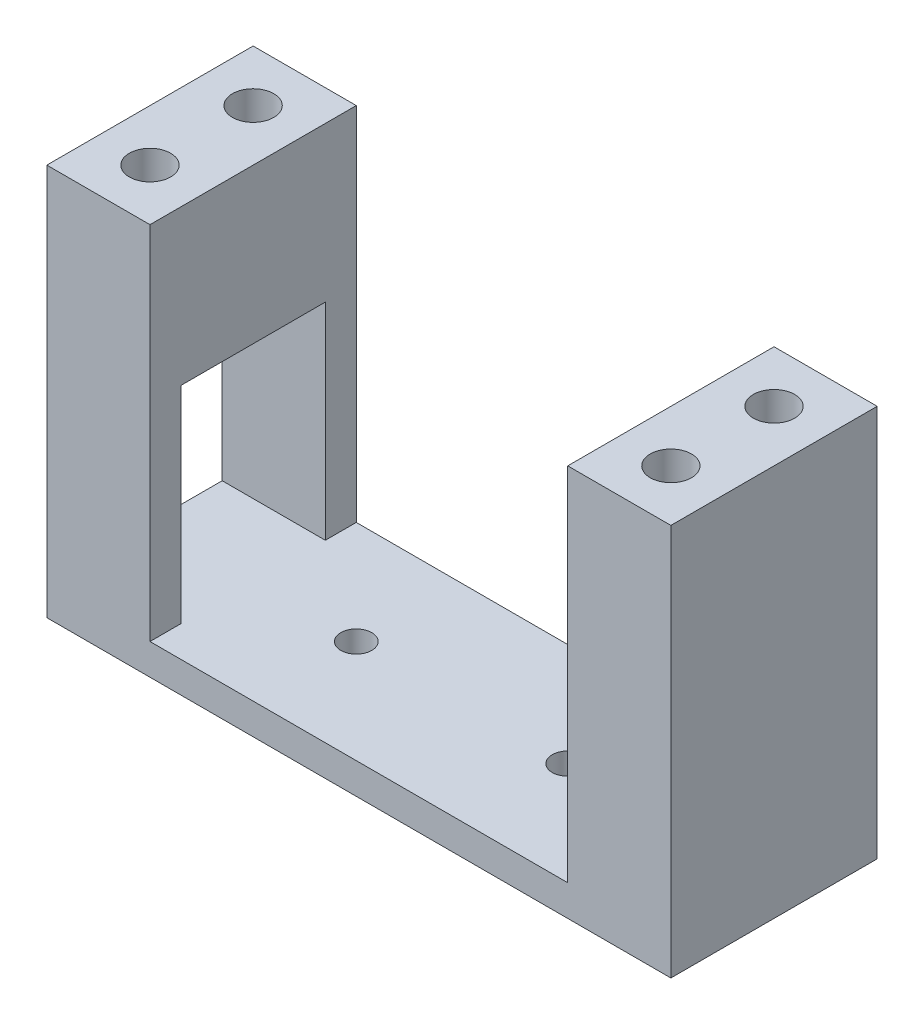
SolidWorks part; units mm, degrees
ref_plane "Спереди" through (0, 0, 0) normal (0, 0, 1) x (1, 0, 0)
ref_plane "Сверху" through (0, 0, 0) normal (0, 1, 0) x (1, 0, 0)
ref_plane "Справа" through (0, 0, 0) normal (1, 0, 0) x (0, 0, -1)
sketch "Эскиз2" plane through (0, 0, 0) normal (0, 0, 1) x (1, 0, 0)
  line L0 (0, 0) -> (60.5, 0)
  line L1 (60.5, 0) -> (60.5, 38)
  line L2 (60.5, 38) -> (50.5, 38)
  line L3 (50.5, 38) -> (50.5, 3)
  line L4 (50.5, 3) -> (10, 3)
  line L5 (10, 3) -> (10, 38)
  line L6 (10, 38) -> (0, 38)
  line L7 (0, 38) -> (0, 0)
  dimension "D1" = 10
  dimension "D2" = 3
  dimension "D3" = 35
  dimension "D4" = 40.5
extrude "Бобышка-Вытянуть2" add sketch "Эскиз2" along normal blind 20
sketch "Эскиз3" plane through (0, 0, 0) normal (-1, 0, 0) x (0, 0, 1)
  line L0 (3, 3) -> (17, 3)
  line L1 (17, 3) -> (17, 23)
  line L2 (17, 23) -> (3, 23)
  line L3 (3, 23) -> (3, 3)
  line L4 (20, 0) -> (0, 0) construction
  line L5 (20, 38) -> (0, 38) construction
  line L6 (20, 38) -> (20, 0) construction
  line L8 (0, 38) -> (0, 0) construction
  dimension "D1" = 3
  dimension "D2" = 15
  dimension "D3" = 3
  dimension "D4" = 3
extrude "Вырез-Вытянуть1" cut sketch "Эскиз3" against normal up to next
sketch "Эскиз4" plane through (0, 38, 0) normal (0, 1, 0) x (1, 0, 0)
  line L0 (5, 0) -> (5, -20) construction
  line L1 (10, 0) -> (0, 0) construction
  line L2 (10, -20) -> (0, -20) construction
  line L3 (55.5, 0) -> (55.5, -20) construction
  line L4 (60.5, 0) -> (50.5, 0) construction
  line L5 (60.5, -20) -> (50.5, -20) construction
  circle A0 centre (5, -5) radius 2
  circle A1 centre (5, -15) radius 2
  circle A2 centre (55.5, -5) radius 2
  circle A3 centre (55.5, -15) radius 2
  point P20 (0, 0)
  point P21 (0, 0)
  dimension "D1" = 4
  dimension "D2" = 5
  dimension "D3" = 5
extrude "Вырез-Вытянуть2" cut sketch "Эскиз4" against normal blind 10
sketch "Эскиз5" plane through (0, 0, 0) normal (0, -1, 0) x (1, 0, 0)
  line L0 (0, 10) -> (20, 10) construction
  line L3 (0, 20) -> (0, 0) construction
  line L4 (40.5, 10) -> (60.5, 10) construction
  line L5 (60.5, 20) -> (60.5, 0) construction
  circle A0 centre (20, 10) radius 1.5
  circle A1 centre (40.5, 10) radius 1.5
  dimension "D2" = 3
  dimension "D1" = 20
extrude "Вырез-Вытянуть3" cut sketch "Эскиз5" against normal blind 10
